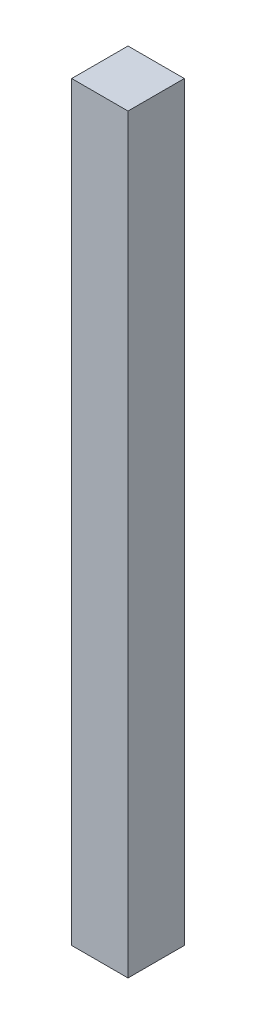
SolidWorks part; units mm, degrees
ref_plane "Alzado" through (0, 0, 0) normal (0, 0, 1) x (1, 0, 0)
ref_plane "Planta" through (0, 0, 0) normal (0, 1, 0) x (1, 0, 0)
ref_plane "Vista lateral" through (0, 0, 0) normal (1, 0, 0) x (0, 0, -1)
sketch "Croquis1" plane through (0, 0, 0) normal (0, 1, 0) x (1, 0, 0)
  line L1 (-15, -15) -> (15, -15)
  line L2 (-15, -15) -> (-15, 15)
  line L3 (-15, 15) -> (15, 15)
  line L4 (15, -15) -> (15, 15)
  line L5 (-15, -15) -> (15, 15) construction
  line L6 (-15, 15) -> (15, -15) construction
  point P0 (0, 0)
  dimension "D1" = 30
extrude "Saliente-Extruir1" add sketch "Croquis1" along normal blind 400
